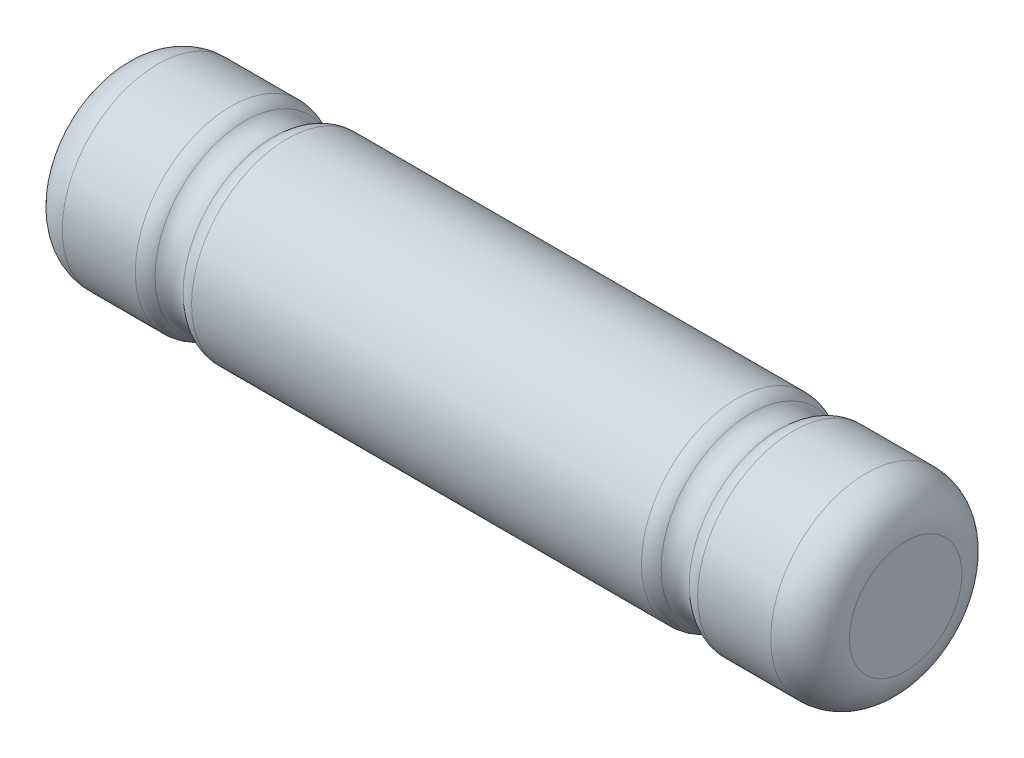
SolidWorks part; units mm, degrees
ref_plane "Front Plane" through (0, 0, 0) normal (0, 0, 1) x (1, 0, 0)
ref_plane "Top Plane" through (0, 0, 0) normal (0, 1, 0) x (1, 0, 0)
ref_plane "Right Plane" through (0, 0, 0) normal (1, 0, 0) x (0, 0, -1)
sketch "Sketch2" plane through (0, 0, 0) normal (0, 0, 1) x (1, 0, 0)
  line L0 (-6.3, 1.7) -> (-5, 1.7)
  line L1 (-7, 0) -> (7, 0)
  line L2 (-7, 0) -> (-7, 1)
  line L4 (7, 0) -> (7, 1)
  line L5 (0, 0) -> (0, 4.4662) construction
  line L6 (-4, 1.7) -> (4, 1.7)
  line L7 (5, 1.7) -> (6.3, 1.7)
  arc A0 (-7, 1) -> (-6.3, 1.7) centre (-6.3, 1) cw
  arc A1 (6.3, 1.7) -> (7, 1) centre (6.3, 1) cw
  arc A2 (-5, 1.7) -> (-4.75, 1.6) centre (-5, 1.3375) cw
  arc A3 (-4.75, 1.6) -> (-4.25, 1.6) centre (-4.5, 1.8625) ccw
  arc A4 (-4.25, 1.6) -> (-4, 1.7) centre (-4, 1.3375) cw
  arc A5 (4.25, 1.6) -> (4, 1.7) centre (4, 1.3375) ccw
  arc A6 (4.75, 1.6) -> (4.25, 1.6) centre (4.5, 1.8625) cw
  arc A7 (5, 1.7) -> (4.75, 1.6) centre (5, 1.3375) ccw
  point P27 (-4.5, 1.5)
  dimension "D3" = 0.7
  dimension "D1" = 14
  dimension "D2" = 1.7
  dimension "D4" = 9
  dimension "D5" = 1.5
  dimension "D6" = 1
revolve "Revolve1" add sketch "Sketch2" angle 360 about L1
ref_plane "Plane1" through (-4.75, 0, 0) normal (1, 0, 0) x (0, 0, -1)
ref_plane "Plane2" through (4.75, 0, 0) normal (1, 0, 0) x (0, 0, -1)
equation "\"D2@Sketch2\"=3.4/2"
equation "\"D5@Sketch2\"=\"D2@Sketch2\"-0.2"
